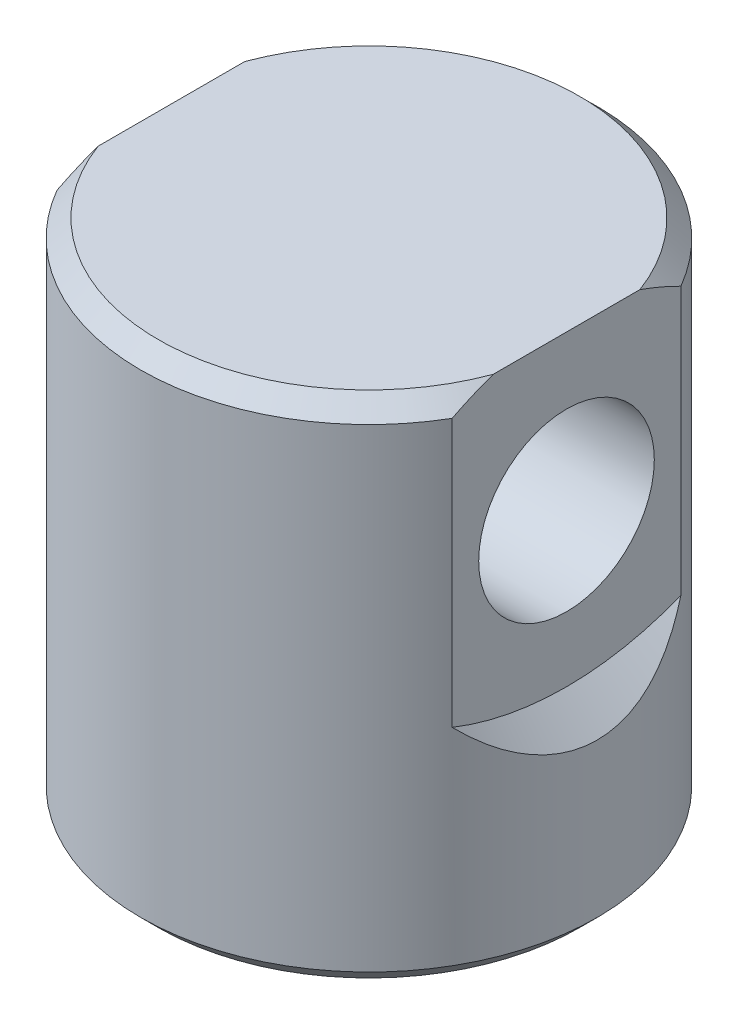
SolidWorks part; units mm, degrees
ref_plane "Plan1" through (0, 0, 0) normal (0, 0, 1) x (1, 0, 0)
ref_plane "Plan2" through (0, 0, 0) normal (0, 1, 0) x (1, 0, 0)
ref_plane "Plan3" through (0, 0, 0) normal (1, 0, 0) x (0, 0, -1)
sketch "Esquisse1" plane through (0, 0, 0) normal (0, 0, 1) x (1, 0, 0)
  line L0 (0, 0) -> (0, 100) construction
  line L1 (0, 0) -> (13, 0)
  line L2 (13, 0) -> (13, 29)
  line L3 (13, 29) -> (0, 29)
  line L4 (0, 29) -> (0, 0)
  dimension "D1" = 29
  dimension "D2" = 13
revolve "Base-Révolution" add sketch "Esquisse1" angle 360 about L0
sketch "Esquisse2" plane through (0, 0, 0) normal (0, -1, 0) x (1, 0, 0)
  circle A0 centre (0, 0) radius 11.5
extrude "Enlèv. mat.-Extru.1" cut sketch "Esquisse2" against normal blind 4
chamfer "Chanfrein1" distance 1 angle 45
sketch "Esquisse3" plane through (0, 0, 0) normal (0, 1, 0) x (1, 0, 0)
  line L0 (0, 0) -> (0, 20) construction
  line L1 (0, 12.2) -> (16.5, 12.2)
  line L2 (16.5, 12.2) -> (21.5, 17.2)
  line L3 (21.5, 17.2) -> (0, 17.2)
  line L4 (0, 17.2) -> (0, 12.2)
  dimension "D1" = 12.2
  dimension "D2" = 135
  dimension "D3" = 16.5
  dimension "D4" = 5
revolve "Enlèvement de matière-Révolution1" cut sketch "Esquisse3" angle 360 about L0
sketch "Esquisse4" plane through (0, 4, 0) normal (0, -1, 0) x (1, 0, 0)
  circle A0 centre (0, 0) radius 8
extrude "Enlèv. mat.-Extru.2" cut sketch "Esquisse4" against normal blind 10
sketch "Esquisse6" plane through (0, 0, 0) normal (1, 0, 0) x (0, 0, -1)
  line L0 (0, -0.3896) -> (0, 30.5607) construction
  line L1 (0, 4) -> (0, 0) construction
  line L2 (12, 29) -> (-12, 29) construction
  circle A0 centre (0, 20.2) radius 5
  dimension "D2" = 10
  dimension "D1" = 8.8
extrude "Enlèv. mat.-Extru.4" cut sketch "Esquisse6" against normal through all and the other way through all
sketch "Esquisse7" plane through (0, 29, 0) normal (0, 1, 0) x (-1, 0, 0)
  line L0 (0, 0) -> (-15.0699, 0) construction
  line L1 (12, 0) -> (-12, 0) construction
  line L3 (-11.25, 0) -> (-11.25, 17.5)
  line L4 (11.25, 0) -> (11.25, 17.5)
  line L5 (-11.25, 17.5) -> (-16.25, 22.5)
  line L6 (11.25, 17.5) -> (16.25, 22.5)
  line L7 (-16.25, 22.5) -> (-16.25, 0)
  line L8 (16.25, 22.5) -> (16.25, 0)
  line L9 (-16.25, 0) -> (-11.25, 0)
  line L10 (16.25, 0) -> (11.25, 0)
  dimension "D1" = 135
  dimension "D2" = 5
  dimension "D3" = 135
  dimension "D4" = 17.5
  dimension "D5" = 22.5
  dimension "D6" = 11.25
  dimension "D7" = 5
revolve "Enlèvement de matière-Révolution2" cut sketch "Esquisse7" angle 360 about L0
sketch "Esquisse8" plane through (0, 0, -12.2) normal (0, 0, -1) x (-1, 0, 0)
  line L0 (0, 4) -> (0, 0) construction
  line L1 (-12, 0) -> (12, 0) construction
  circle A0 centre (0, 8) radius 3
  dimension "D1" = 6
  dimension "D2" = 8
extrude "Enlèv. mat.-Extru.5" cut sketch "Esquisse8" against normal up to next
